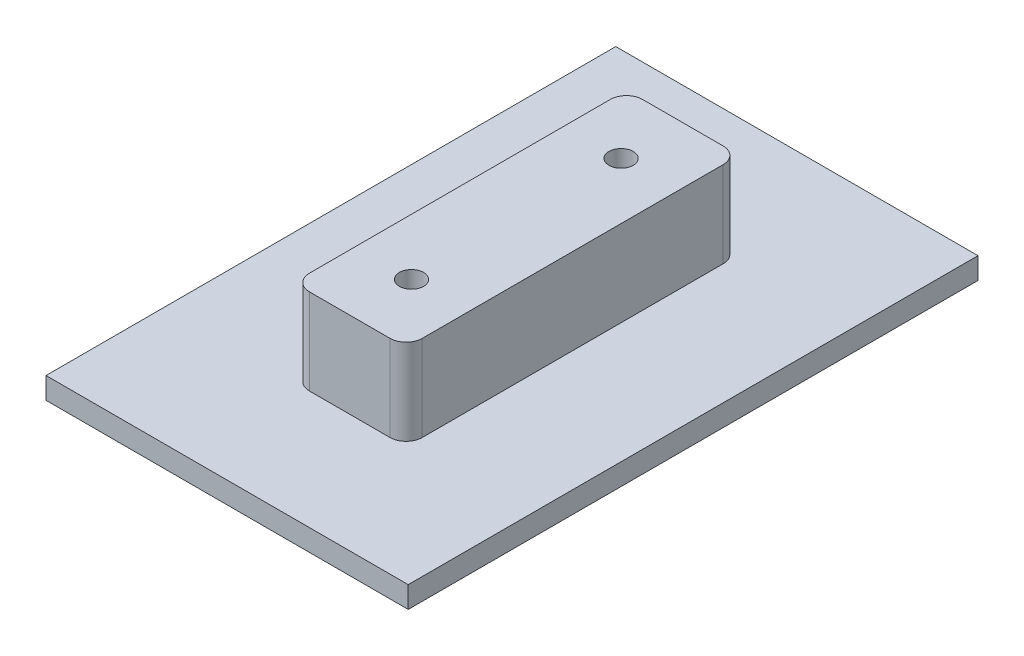
SolidWorks part; units mm, degrees
material "Alloy Steel"
ref_plane "Front Plane" through (0, 0, 0) normal (0, 0, 1) x (1, 0, 0)
ref_plane "Top Plane" through (0, 0, 0) normal (0, 1, 0) x (1, 0, 0)
ref_plane "Right Plane" through (0, 0, 0) normal (1, 0, 0) x (0, 0, -1)
other "Configuration Table"
sketch "Sketch1" plane through (0, 0, 0) normal (0, 1, 0) x (1, 0, 0)
  line L0 (-107.0007, 168.3199) -> (107.0007, -168.3199) construction
  line L1 (-107.0007, 168.3199) -> (107.0007, 168.3199)
  line L2 (-107.0007, 168.3199) -> (-107.0007, -168.3199)
  line L3 (-107.0007, -168.3199) -> (107.0007, -168.3199)
  line L4 (107.0007, 168.3199) -> (107.0007, -168.3199)
extrude "Extrude1" add sketch "Sketch1" against normal blind 12.7
sketch "Sketch2" plane through (0, 0, 0) normal (0, 1, 0) x (-1, 0, 0)
  line L32 (-35.8733, 88.9) -> (-35.8733, -88.9)
  line L33 (21.2767, 98.425) -> (-26.3483, 98.425)
  line L34 (30.8017, -88.9) -> (30.8017, 88.9)
  line L35 (-26.3483, -98.425) -> (21.2767, -98.425)
  line L36 (-35.8733, 88.9) -> (-35.8733, -88.9)
  line L37 (21.2767, 98.425) -> (-26.3483, 98.425)
  line L38 (30.8017, -88.9) -> (30.8017, 88.9)
  line L39 (-26.3483, -98.425) -> (21.2767, -98.425)
  circle A0 centre (-2.5358, 61.9125) radius 7.1437
  circle A1 centre (-2.5358, -61.9125) radius 7.1437
  arc A2 (4.608, -61.9125) -> (-9.6795, -61.9125) centre (-2.5358, -61.9125) ccw construction
  arc A3 (-9.6795, 61.9125) -> (4.608, 61.9125) centre (-2.5358, 61.9125) ccw construction
  arc A36 (-26.3483, 98.425) -> (-35.8733, 88.9) centre (-26.3483, 88.9) ccw
  arc A37 (30.8017, 88.9) -> (21.2767, 98.425) centre (21.2767, 88.9) ccw
  arc A38 (21.2767, -98.425) -> (30.8017, -88.9) centre (21.2767, -88.9) ccw
  arc A39 (-35.8733, -88.9) -> (-26.3483, -98.425) centre (-26.3483, -88.9) ccw
  arc A40 (-26.3483, 98.425) -> (-35.8733, 88.9) centre (-26.3483, 88.9) ccw
  arc A41 (30.8017, 88.9) -> (21.2767, 98.425) centre (21.2767, 88.9) ccw
  arc A42 (21.2767, -98.425) -> (30.8017, -88.9) centre (21.2767, -88.9) ccw
  arc A43 (-35.8733, -88.9) -> (-26.3483, -98.425) centre (-26.3483, -88.9) ccw
  dimension "D1" = 6.35
extrude "Extrude2" add sketch "Sketch2" along normal up to surface (50.7448 mm away)
